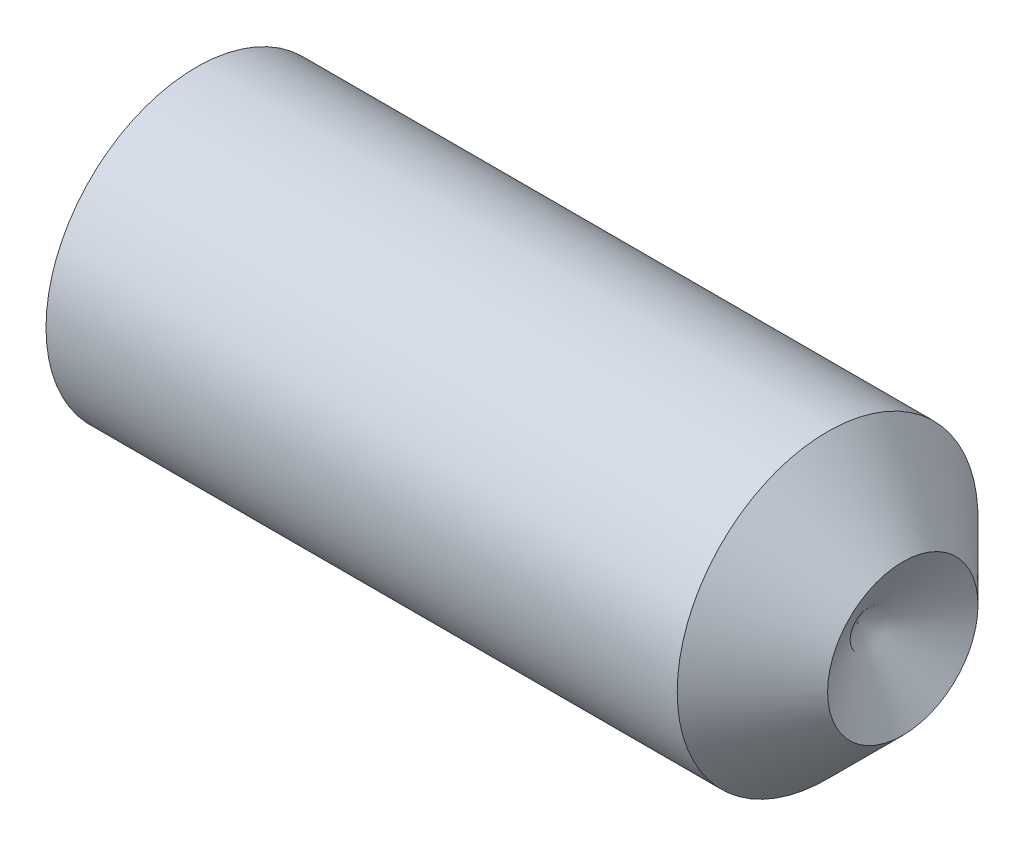
SolidWorks part; units mm, degrees
revolve "BaseBody" add sketch "BodySke" angle 360 about L5
sketch "BodySke" plane through (0, 0, 0) normal (0, 0, 1) x (1, 0, 0)
  line L0 (0, 0) -> (0, 2.055)
  line L1 (0, 2.055) -> (0.2569, 2.5)
  line L2 (0.2569, 2.5) -> (10.75, 2.5)
  line L3 (10.75, 2.5) -> (12, 1.25)
  line L4 (11.2489, 0) -> (0, 0)
  line L5 (-12.7, 0) -> (88.9, 0) construction
  line L6 (11.2489, 0) -> (12, 1.25)
  line L7 (12, 1.25) -> (12, 10.775) construction
  line L8 (0, -2.055) -> (0.2569, -2.5) construction
  line L9 (11.2489, 0) -> (12, -1.25) construction
  line L10 (10.75, -2.5) -> (12, -1.25) construction
  line L11 (0.8, 15.875) -> (0.8, -3.175) construction
  dimension "Diameter" = 5
  dimension "Drive_ch_ang" = 60
  dimension "Minor_dia" = 4.11
  dimension "Cup_nose_ang" = 45
  dimension "Cup_ang" = 118
  dimension "Cup_dia" = 2.5
  dimension "Advance" = 0.8
cosmetic thread "ThreadCosmetic" [suppressed] parameters "Thread_minor"=4.11
ref_plane "Plane1" through (0, 0, 0) normal (0, 0, 1) x (1, 0, 0)
ref_plane "Plane2" through (0, 0, 0) normal (0, 1, 0) x (1, 0, 0)
ref_plane "Plane3" through (0, 0, 0) normal (1, 0, 0) x (0, 0, -1)
other "Configuration Table"
sketch "Sketch2" plane through (0, 0, 0) normal (-1, 0, 0) x (0, 0, 1)
  line L0 (0.7217, 1.25) -> (-0.7217, 1.25)
  line L1 (-0.7217, 1.25) -> (-1.4434, 0)
  line L2 (0.7217, 1.25) -> (1.4434, 0)
  line L3 (0.7217, -1.25) -> (1.4434, 0)
  line L4 (0.7217, -1.25) -> (-0.7217, -1.25)
  line L5 (-0.7217, -1.25) -> (-1.4434, 0)
  dimension "Hex_size" = 2.5
  dimension "D2" = 1.25
  dimension "D3" = 1.25
extrude "Hex" cut sketch "Sketch2" against normal blind 2.7
sketch "Sketch4" plane through (0, 4.7709, -0.5249) normal (-1, 0, 0) x (0, 0, 1)
  line L0 (0.5249, -4.7709) -> (1.9854, -4.7709)
  line L1 (0.5249, -4.7709) -> (6.6732, -1.2211) construction
  line L2 (0.5249, -4.7709) -> (1.2551, -3.506)
  line L3 (1.7257, -4.4442) -> (1.9182, -4.333)
  line L4 (1.4082, -3.8943) -> (1.6007, -3.7831)
  arc A0 (1.7257, -4.4442) -> (1.4082, -3.8943) centre (0.5249, -4.7709) ccw
  arc A1 (1.9854, -4.7709) -> (1.9182, -4.333) centre (0.5249, -4.7709) ccw
  arc A2 (1.2551, -3.506) -> (1.6007, -3.7831) centre (0.5249, -4.7709) cw
  circle A3 centre (0.5249, -4.7709) radius 1.2445 construction
  circle A4 centre (0.5249, -4.7709) radius 1.4605 construction
  dimension "Spline_n_dim" = 2.489
  dimension "Spline_m_dim" = 2.921
  dimension "D1" = 30
  dimension "Spline_a_dim" = 60
  dimension "Spline_p_dim" = 0.635
  dimension "D3" = 0.3175
extrude "Spline6" [suppressed] cut sketch "Sketch4" against normal blind 2.3
pattern_circular "CirPattern1" [suppressed] count 6 every 60 about axis through (-12.7, 0, 0) along (1, 0, 0)
sketch "Sketch5" plane through (0, 1.5227, 6.1981) normal (-1, 0, 0) x (0, 0, 1)
  line L0 (-6.1981, -1.5227) -> (-4.7376, -1.5227)
  line L1 (-6.1981, -1.5227) -> (-1.178, 3.4975) construction
  line L2 (-6.1981, -1.5227) -> (-6.1981, -0.0622)
  line L3 (-5.0936, -0.8672) -> (-4.9655, -0.7391)
  line L4 (-5.5426, -0.4182) -> (-5.4146, -0.2901)
  line L5 (-5.5426, -0.4182) -> (-5.0936, -0.8672)
  arc A1 (-4.7376, -1.5227) -> (-4.9655, -0.7391) centre (-6.1981, -1.5227) ccw
  arc A2 (-6.1981, -0.0622) -> (-5.4146, -0.2901) centre (-6.1981, -1.5227) cw
  circle A3 centre (-6.1981, -1.5227) radius 1.2445 construction
  circle A4 centre (-6.1981, -1.5227) radius 1.4605 construction
  dimension "Spline_n_dim" = 2.489
  dimension "Spline_m_dim" = 2.921
  dimension "Spline_p_dim" = 0.635
  dimension "D3" = 0.3175
  dimension "D1" = 45
  dimension "Spline_a_dim" = 90
extrude "Spline4" [suppressed] cut sketch "Sketch5" against normal blind 2.3
pattern_circular "CirPattern2" [suppressed] count 4 every 90 about axis through (-12.7, 0, 0) along (1, 0, 0)
sketch "ThdSchSke" plane through (0, 0, 0) normal (0, 0, 1) x (1, 0, 0)
  line L0 (0.2569, -2.055) -> (-0.0547, -2.5)
  line L1 (0.2569, -2.055) -> (0.5685, -2.5)
  line L2 (0.5685, -2.5) -> (0.5685, -3.125)
  line L3 (-3.175, 0) -> (5.1513, 0) construction
  line L4 (0.2569, 2.5) -> (0.2569, -2.5) construction
  line L5 (0.5685, -3.125) -> (-0.0547, -3.125)
  line L6 (-0.0547, -3.125) -> (-0.0547, -2.5)
  dimension "Thread_minor" = 4.11
  dimension "Diameter" = 5
revolve "ThreadSchematic" [suppressed] cut sketch "ThdSchSke" angle 360 about L3
pattern_linear "ThdSchPat" [suppressed]
equation "\"D2@Sketch2\" = \"Hex_size@Sketch2\" / 2"
equation "\"D3@Sketch2\" = \"Hex_size@Sketch2\" / 2"
equation "\"Thread_minor@ThreadCosmetic\" = \"Minor_dia@BodySke\""
equation "\"D1@Sketch4\" = \"Spline_a_dim@Sketch4\" / 2"
equation "\"D3@Sketch4\" = \"Spline_p_dim@Sketch4\" / 2"
equation "\"D2@CirPattern1\" = \"Spline_a_dim@Sketch4\""
equation "\"Num_teeth@CirPattern1\" = 360 / \"D2@CirPattern1\""
equation "\"Spline_a_dim@Sketch5\" = 90"
equation "\"Spline_p_dim@Sketch5\" = \"Spline_p_dim@Sketch4\""
equation "\"Spline_m_dim@Sketch5\" = \"Spline_m_dim@Sketch4\""
equation "\"Spline_n_dim@Sketch5\" = \"Spline_n_dim@Sketch4\""
equation "\"D1@Sketch5\" = \"Spline_a_dim@Sketch5\" / 2"
equation "\"D3@Sketch5\" = \"Spline_p_dim@Sketch5\" / 2"
equation "\"Key_eng@Spline4\" = \"Key_eng@Spline6\""
equation "\"Thread_minor@ThdSchSke\" = \"Thread_minor@ThreadCosmetic\""
equation "\"Diameter@ThdSchSke\" = \"Diameter@BodySke\""
equation "\"Overcut@ThdSchSke\" = \"Diameter@BodySke\" * 1.25"
equation "\"Num_threads@ThdSchPat\" = int( (\"Length@BodySke\" - ( ( ( \"Diameter@BodySke\" - \"Minor_dia@BodySke\" ) * 0.5 ) / tan( \"Drive_ch_ang@BodySke\" * 0.017453292 ) ) - ( ( ( \"Diameter@BodySke\" - \"Cup_dia@BodySke\" ) * 0.5 ) * tan( \"Cup_nose_ang@BodySke\" * 0.017453292 ) ) ) / \"Advance@BodySke\" + 0.999 )  + 1"
equation "\"Advance@ThdSchPat\" = (\"Length@BodySke\" - ( ( ( \"Diameter@BodySke\" - \"Minor_dia@BodySke\" ) * 0.5 ) / tan( \"Drive_ch_ang@BodySke\" * 0.017453292 ) ) - ( ( ( \"Diameter@BodySke\" - \"Cup_dia@BodySke\" ) * 0.5 ) * tan( \"Cup_nose_ang@BodySke\" * 0.017453292 ) ) ) /  (\"Num_threads@ThdSchPat\" - 1) 'relax it"
equation "' \"Num_threads@ThdSchPat\" = \"Num_threads@ThdSchPat\" - sgn( \"Num_threads@ThdSchPat\" - 1) '---chamfered tips only---"
